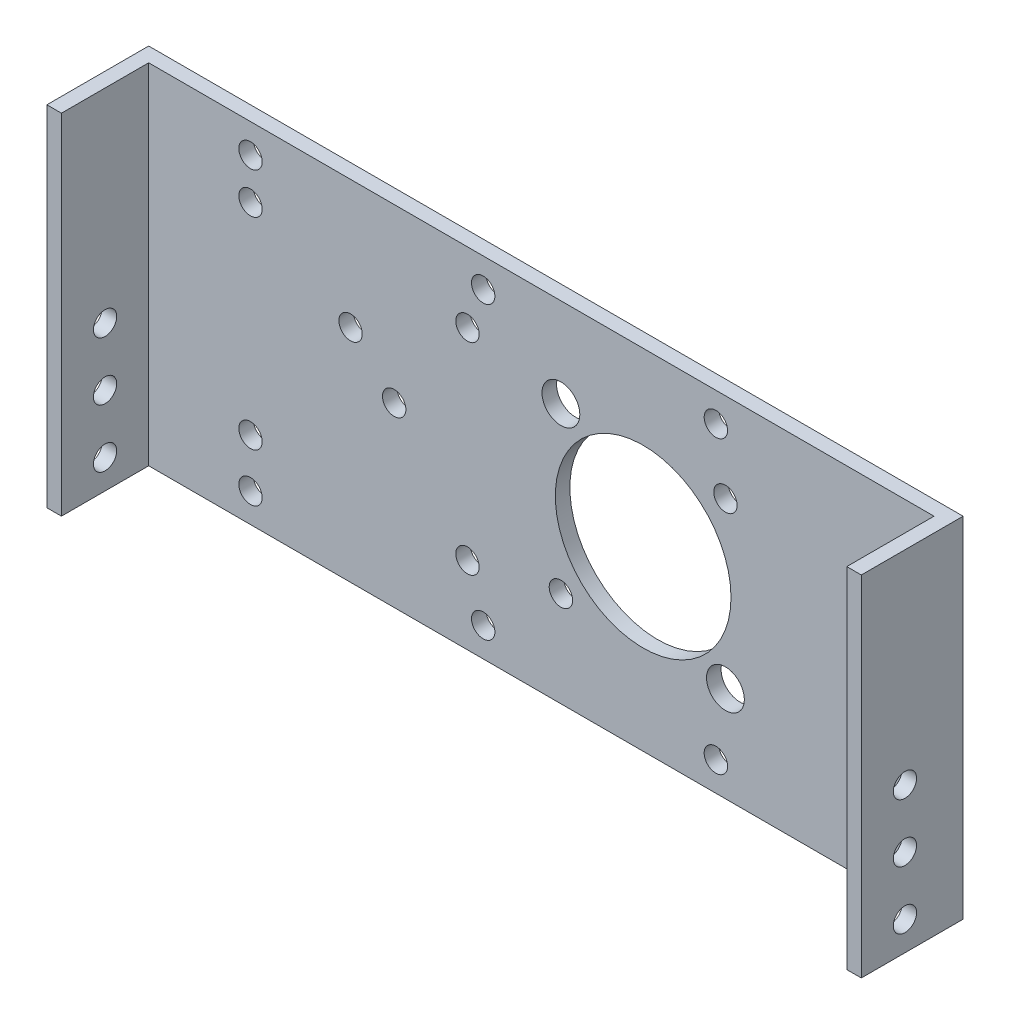
SolidWorks part; units mm, degrees
ref_plane "Front Plane" through (0, 0, 0) normal (0, 0, 1) x (1, 0, 0)
ref_plane "Top Plane" through (0, 0, 0) normal (0, 1, 0) x (1, 0, 0)
ref_plane "Right Plane" through (0, 0, 0) normal (1, 0, 0) x (0, 0, -1)
sketch "Sketch1" plane through (0, 0, 0) normal (0, 0, 1) x (1, 0, 0)
  line L1 (-37.4695, 3.5097) -> (-37.4695, 79.7097)
  line L2 (140.3305, 79.7097) -> (140.3305, 3.5097)
  line L6 (-37.4695, 79.7097) -> (140.3305, 79.7097)
  line L7 (-37.4695, 3.5097) -> (140.3305, 3.5097)
  circle A0 centre (89.5305, 9.8597) radius 2.5527
  circle A1 centre (89.5305, 73.3597) radius 2.5527
  circle A2 centre (-12.0695, 73.3597) radius 2.5527
  circle A9 centre (-12.0695, 64.4274) radius 2.5527
  circle A13 centre (38.7305, 73.3597) radius 2.5527
  circle A14 centre (35.3015, 64.4274) radius 2.5527
  circle A15 centre (9.7742, 51.7274) radius 2.5527
  circle A16 centre (19.2992, 42.2024) radius 2.5527
  circle A18 centre (-12.0695, 20.4337) radius 2.5527
  circle A23 centre (35.3015, 20.4337) radius 2.5527
  circle A24 centre (38.7305, 9.8597) radius 2.5527
  circle A25 centre (55.695, 24.3332) radius 2.5527
  circle A26 centre (55.695, 60.2542) radius 4.1275
  circle A27 centre (91.6161, 60.2542) radius 2.5527
  circle A29 centre (91.6161, 24.3332) radius 4.1275
  circle A30 centre (73.6555, 42.2024) radius 19.177
  circle A31 centre (-12.0695, 9.8597) radius 2.5527
  circle A32 centre (121.2805, 42.2024) radius 2.5527
  point P2 (0, 0)
  point P11 (0, 0)
  point P12 (0, 0)
  point P13 (0, 0)
  point P14 (0, 0)
  point P16 (0, 0)
  point P17 (0, 0)
  dimension "D4" = 5.1054
  dimension "D22" = 8.255
  dimension "D23" = 38.354
  dimension "D1" = 177.8
  dimension "D2" = 76.2
  dimension "D6" = 50.8
  dimension "D7" = 35.921
  dimension "D8" = 35.921
  dimension "D9" = 17.9605
  dimension "D10" = 18.0518
  dimension "D11" = 43.9937
  dimension "D12" = 47.371
  dimension "D13" = 25.5273
  dimension "D14" = 12.7
  dimension "D15" = 9.525
  dimension "D16" = 9.525
  dimension "D5" = 50.8
  dimension "D19" = 63.5
  dimension "D20" = 25.4
  dimension "D21" = 6.35
  dimension "D24" = 25.4
  dimension "D25" = 16.9239
  dimension "D26" = 19.05
  dimension "D17" = 67.7645
  dimension "D18" = 3.8995
extrude "Boss-Extrude1" add sketch "Sketch1" along normal blind 3.175
sketch "Sketch2" plane through (0, 0, 3.175) normal (0, 0, 1) x (1, 0, 0)
  line L0 (-37.4695, 3.5097) -> (140.3305, 3.5097) construction
  line L1 (-37.4695, 79.7097) -> (-34.2945, 79.7097)
  line L2 (-37.4695, 79.7097) -> (-37.4695, 3.5097)
  line L3 (-37.4695, 3.5097) -> (-34.2945, 3.5097)
  line L4 (-34.2945, 79.7097) -> (-34.2945, 3.5097)
  line L6 (140.3305, 79.7097) -> (137.1555, 79.7097)
  line L7 (140.3305, 79.7097) -> (140.3305, 3.5097)
  line L8 (140.3305, 3.5097) -> (137.1555, 3.5097)
  line L9 (137.1555, 79.7097) -> (137.1555, 3.5097)
  point P11 (0, 0)
  dimension "D1" = 3.175
extrude "Boss-Extrude2" add sketch "Sketch2" along normal blind 19.05
sketch "Sketch3" plane through (140.3305, 0, 0) normal (1, 0, 0) x (0, 0, -1)
  line L0 (-22.225, 3.5097) -> (0, 3.5097) construction
  line L1 (0, 3.5097) -> (0, 79.7097) construction
  circle A0 centre (-12.7, 35.2597) radius 2.54
  circle A1 centre (-12.7, 22.5597) radius 2.54
  circle A2 centre (-12.7, 9.8597) radius 2.54
  point P4 (0, 0)
  point P9 (0, 0)
  dimension "D1" = 6.35
  dimension "D5" = 5.08
  dimension "D2" = 12.7
  dimension "D3" = 12.7
  dimension "D4" = 12.7
extrude "Cut-Extrude1" cut sketch "Sketch3" against normal through all
equation "\"D12@Sketch1\"=1.664+0.201"
